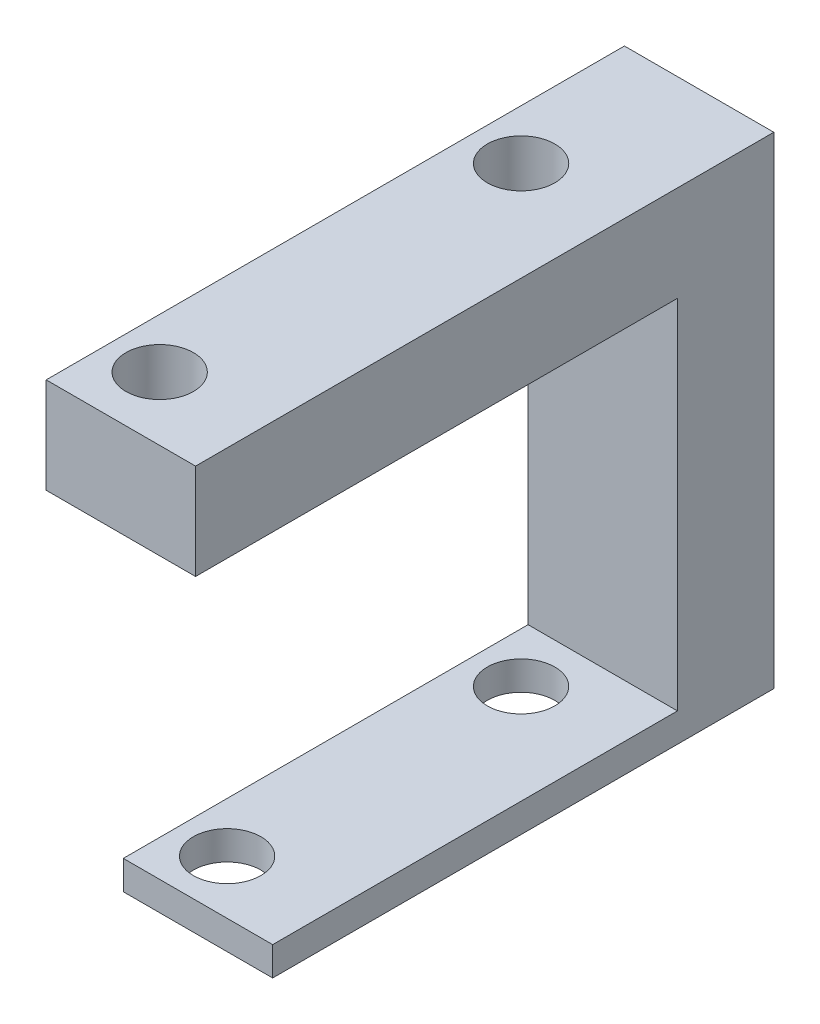
SolidWorks part; units mm, degrees
ref_plane "Front Plane" through (0, 0, 0) normal (0, 0, 1) x (1, 0, 0)
ref_plane "Top Plane" through (0, 0, 0) normal (0, 1, 0) x (1, 0, 0)
ref_plane "Right Plane" through (0, 0, 0) normal (1, 0, 0) x (0, 0, -1)
sketch "Sketch1" plane through (0, 0, 0) normal (1, 0, 0) x (0, 0, -1)
  line L0 (-10.5475, 32.5993) -> (-10.5475, 7.1993)
  line L1 (-41.0275, 32.5993) -> (-10.5475, 32.5993)
  line L2 (-41.0275, 32.5993) -> (-41.0275, 27.5582)
  line L3 (-41.0275, 27.5582) -> (-15.6275, 27.5582)
  line L6 (-15.6275, 27.5582) -> (-15.6275, 8.7233)
  line L9 (-10.5475, 7.1993) -> (-36.9635, 7.1993)
  line L11 (-15.6275, 8.7233) -> (-36.9635, 8.7233)
  line L12 (-36.9635, 7.1993) -> (-36.9635, 8.7233)
  dimension "D1" = 5.0411
  dimension "D2" = 1.524
  dimension "D3" = 21.336
  dimension "D4" = 10.5475
  dimension "D6" = 5.08
  dimension "D7" = 7.1993
  dimension "D8" = 41.0275
extrude "Boss-Extrude1" add sketch "Sketch1" against normal blind 7.874
sketch "Sketch4" plane through (0, 0, 0) normal (0, 1, 0) x (1, 0, 0)
  circle A0 centre (-5.2388, -18.6311) radius 1.778
  circle A1 centre (-5.2388, -34.1251) radius 1.778
  dimension "D1" = 3.556
  dimension "D2" = 15.494
extrude "Cut-Extrude2" cut sketch "Sketch4" along normal blind 20.828
ref_plane "Plane1" through (0, 32.5993, 0) normal (0, 1, 0) x (1, 0, 0)
sketch "Sketch5" plane through (0, 32.5993, 0) normal (0, 1, 0) x (1, 0, 0)
  circle A0 centre (-5.2388, -18.6311) radius 1.778
  circle A1 centre (-5.2388, -37.6811) radius 1.778
  dimension "D1" = 3.556
  dimension "D2" = 19.05
extrude "Cut-Extrude3" cut sketch "Sketch5" against normal blind 6.35
